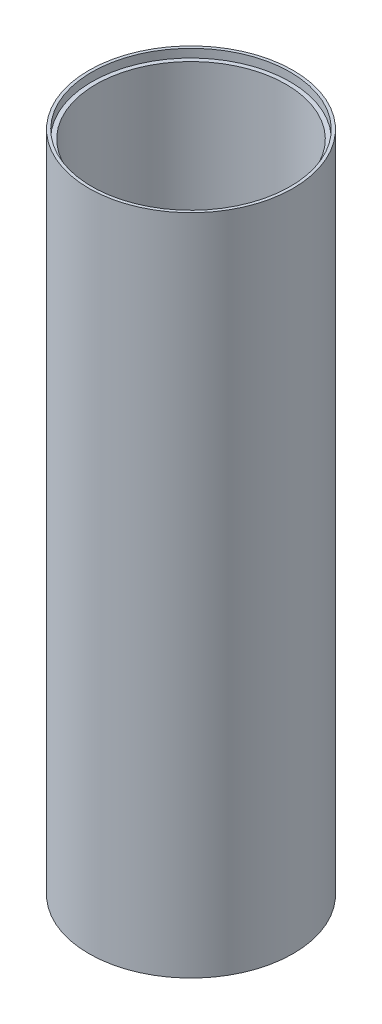
SolidWorks part; units mm, degrees
ref_plane "Front Plane" through (0, 0, 0) normal (0, 0, 1) x (1, 0, 0)
ref_plane "Top Plane" through (0, 0, 0) normal (0, 1, 0) x (1, 0, 0)
ref_plane "Right Plane" through (0, 0, 0) normal (1, 0, 0) x (0, 0, -1)
sketch "Sketch2" plane through (0, 0, 0) normal (0, 0, 1) x (1, 0, 0)
  line L0 (0, 0) -> (-28.575, 0)
  line L1 (-28.575, 0) -> (-28.575, 190.5)
  line L2 (-28.575, 190.5) -> (-29.845, 190.5)
  line L3 (-29.845, 190.5) -> (-29.845, 193.04)
  line L4 (-29.845, 193.04) -> (-30.734, 193.04)
  line L5 (-30.734, 193.04) -> (-30.734, -6.35)
  line L6 (-30.734, -6.35) -> (0, -6.35)
  line L7 (0, -6.35) -> (0, 0) construction
  line L8 (0, 0) -> (0, -6.35)
  dimension "D1" = 190.5
  dimension "D2" = 6.35
  dimension "D3" = 0.889
  dimension "D4" = 1.27
  dimension "D5" = 2.54
  dimension "D6" = 57.15
revolve "Revolve1" add sketch "Sketch2" angle 360 about L7
sketch "Sketch3" plane through (0, 0, 0) normal (0, 1, 0) x (1, 0, 0)
  line L1 (-3.175, -3.175) -> (3.175, -3.175)
  line L2 (-3.175, -3.175) -> (-3.175, 3.175)
  line L3 (-3.175, 3.175) -> (3.175, 3.175)
  line L4 (3.175, -3.175) -> (3.175, 3.175)
  line L5 (-3.175, -3.175) -> (3.175, 3.175) construction
  line L6 (-3.175, 3.175) -> (3.175, -3.175) construction
  point P0 (0, 0)
  dimension "D1" = 6.35
extrude "Cut-Extrude1" cut sketch "Sketch3" against normal through all
